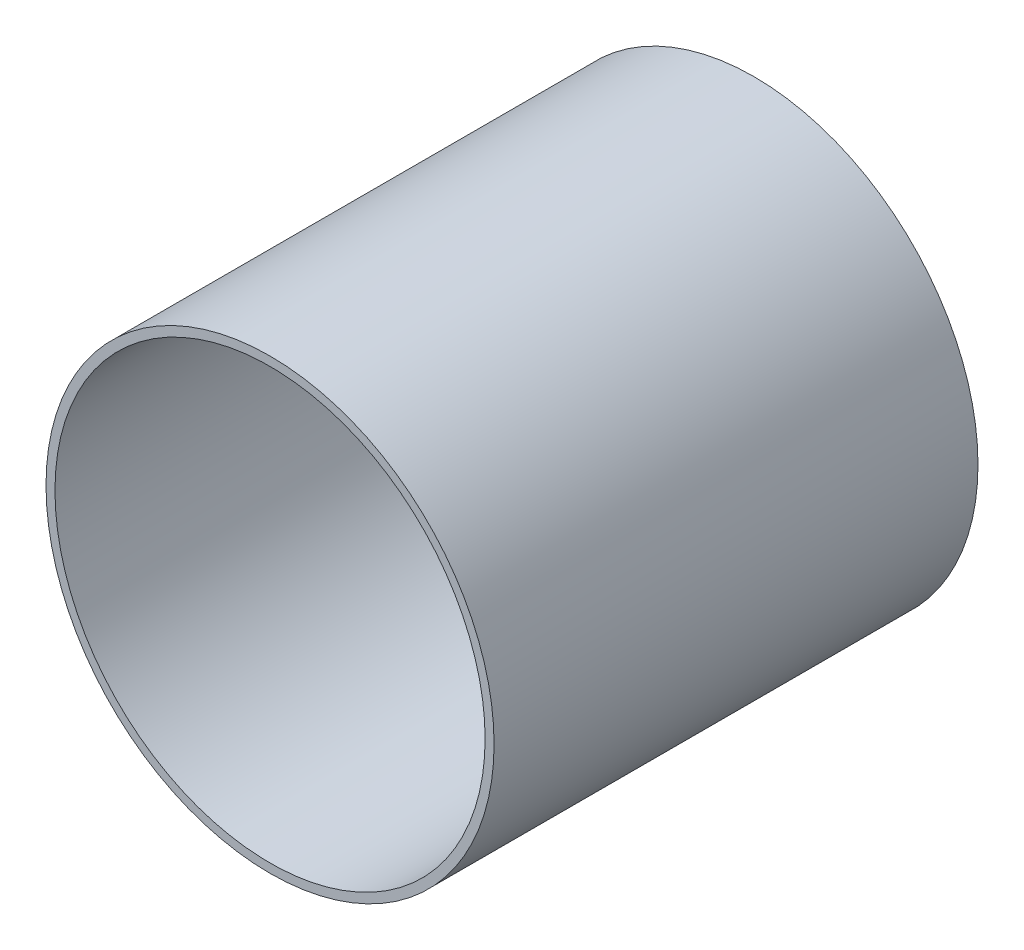
SolidWorks part; units mm, degrees
material "Silicon Dioxide"
ref_plane "Front Plane" through (0, 0, 0) normal (0, 0, 1) x (1, 0, 0)
ref_plane "Top Plane" through (0, 0, 0) normal (0, 1, 0) x (1, 0, 0)
ref_plane "Right Plane" through (0, 0, 0) normal (1, 0, 0) x (0, 0, -1)
sketch "Sketch1" plane through (0, 0, 0) normal (0, 0, 1) x (1, 0, 0)
  circle A0 centre (0, 0) radius 24
  circle A1 centre (0, 0) radius 25
  dimension "D1" = 48
  dimension "D2" = 1
extrude "Boss-Extrude1" add sketch "Sketch1" along normal blind 54
